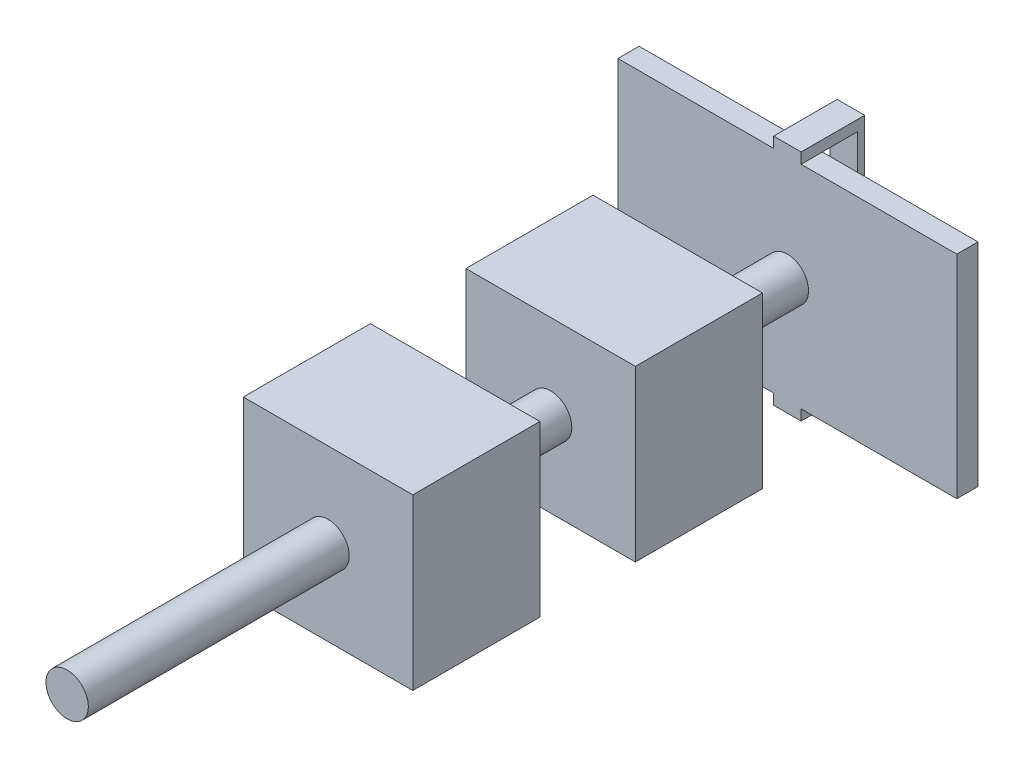
SolidWorks part; units mm, degrees
ref_plane "Front Plane" through (0, 0, 0) normal (0, 0, 1) x (1, 0, 0)
ref_plane "Top Plane" through (0, 0, 0) normal (0, 1, 0) x (1, 0, 0)
ref_plane "Right Plane" through (0, 0, 0) normal (1, 0, 0) x (0, 0, -1)
sketch "Sketch1" plane through (0, 0, 0) normal (0, 0, 1) x (1, 0, 0)
  line L0 (0, 0) -> (0, -20845.1654) construction
  line L1 (0, 0) -> (-20845.1654, 0) construction
  circle A0 centre (0, 0) radius 5
  dimension "D1" = 10
extrude "Boss-Extrude1" add sketch "Sketch1" against normal blind 170
sketch "Sketch2" plane through (0, 0, 0) normal (0, 1, 0) x (1, 0, 0)
  line L0 (0, 170) -> (0, 0) construction
  line L1 (20, 61.5918) -> (-20, 61.5918)
  line L2 (20, 61.5918) -> (20, 91.5918)
  line L3 (20, 91.5918) -> (-20, 91.5918)
  line L4 (-20, 61.5918) -> (-20, 91.5918)
  line L5 (20, 61.5918) -> (-20, 91.5918) construction
  line L6 (20, 91.5918) -> (-20, 61.5918) construction
  line L7 (20, 114.1216) -> (-20, 114.1216)
  line L8 (20, 114.1216) -> (20, 144.1216)
  line L9 (20, 144.1216) -> (-20, 144.1216)
  line L10 (-20, 114.1216) -> (-20, 144.1216)
  line L11 (20, 114.1216) -> (-20, 144.1216) construction
  line L12 (20, 144.1216) -> (-20, 114.1216) construction
  point P0 (0, 76.5918)
  point P5 (0, 129.1216)
  dimension "D1" = 30
  dimension "D2" = 40
  dimension "D3" = 30
  dimension "D4" = 40
extrude "Boss-Extrude2" add sketch "Sketch2" along normal blind 20 and the other way blind 20
sketch "Sketch3" plane through (0, 0, -144.1216) normal (0, 0, -1) x (-1, 0, 0)
  line L1 (17.8814, -18.2528) -> (-17.8814, -18.2528)
  line L2 (17.8814, -18.2528) -> (17.8814, 18.2528)
  line L3 (17.8814, 18.2528) -> (-17.8814, 18.2528)
  line L4 (-17.8814, -18.2528) -> (-17.8814, 18.2528)
  line L5 (17.8814, -18.2528) -> (-17.8814, 18.2528) construction
  line L6 (17.8814, 18.2528) -> (-17.8814, -18.2528) construction
  point P0 (0, 0)
extrude "Cut-Extrude5" cut sketch "Sketch3" against normal blind 16 contours L4 L3 L2 L1
sketch "Sketch5" plane through (0, 0, -128.1216) normal (0, 0, -1) x (-1, 0, 0)
  circle A0 centre (0, 0) radius 5
extrude "Boss-Extrude3" add sketch "Sketch5" along normal blind 16
sketch "Sketch8" plane through (0, 0, -91.5918) normal (0, 0, -1) x (-1, 0, 0)
  line L1 (-17.8814, 18.2528) -> (17.8814, 18.2528)
  line L2 (-17.8814, 18.2528) -> (-17.8814, -18.2528)
  line L3 (-17.8814, -18.2528) -> (17.8814, -18.2528)
  line L4 (17.8814, 18.2528) -> (17.8814, -18.2528)
extrude "Cut-Extrude7" cut sketch "Sketch8" against normal blind 18
sketch "Sketch10" plane through (0, 0, -73.5918) normal (0, 0, -1) x (-1, 0, 0)
  circle A0 centre (0, 0) radius 5
extrude "Boss-Extrude4" add sketch "Sketch10" along normal blind 18
sketch "Sketch11" plane through (0, 0, -170) normal (0, 0, -1) x (-1, 0, 0)
  line L1 (40, -25) -> (-40, -25)
  line L2 (40, -25) -> (40, 25)
  line L3 (40, 25) -> (-40, 25)
  line L4 (-40, -25) -> (-40, 25)
  line L5 (40, -25) -> (-40, 25) construction
  line L6 (40, 25) -> (-40, -25) construction
  point P0 (0, 0)
  dimension "D1" = 80
  dimension "D2" = 50
extrude "Boss-Extrude5" add sketch "Sketch11" along normal blind 5
ref_plane "Plane1" through (0, 0, 0) normal (0, -1, 0) x (-1, 0, 0)
sketch "Sketch12" plane through (0, -25, 0) normal (0, -1, 0) x (1, 0, 0)
  line L4 (40, -170) -> (-40, -170)
  line L5 (-40, -170) -> (-40, -175)
  line L6 (-40, -175) -> (40, -175)
  line L7 (40, -175) -> (40, -170)
  line L8 (40, -170) -> (-40, -170)
  line L9 (-40, -170) -> (-40, -175)
  line L10 (-40, -175) -> (40, -175)
  line L11 (40, -175) -> (40, -170)
  dimension "D1" = 0
ref_plane "Plane2" through (0, 0, -185) normal (0, 0, -1) x (-1, 0, 0)
sketch "Sketch13" plane through (0, 0, -185) normal (0, 0, -1) x (-1, 0, 0)
  line L1 (3.2473, -27.5118) -> (-3.2473, -27.5118)
  line L2 (3.2473, -27.5118) -> (3.2473, 27.5118)
  line L3 (3.2473, 27.5118) -> (-3.2473, 27.5118)
  line L4 (-3.2473, -27.5118) -> (-3.2473, 27.5118)
  line L5 (3.2473, -27.5118) -> (-3.2473, 27.5118) construction
  line L6 (3.2473, 27.5118) -> (-3.2473, -27.5118) construction
  point P0 (0, 0)
sketch "Sketch14" plane through (0, 0, -175) normal (0, 0, -1) x (-1, 0, 0)
  line L4 (-40, 25) -> (-40, -25)
  line L5 (-40, -25) -> (40, -25)
  line L6 (40, -25) -> (40, 25)
  line L7 (40, 25) -> (-40, 25)
  line L8 (-40, 25) -> (-40, -25)
  line L9 (-40, -25) -> (40, -25)
  line L10 (40, -25) -> (40, 25)
  line L11 (40, 25) -> (-40, 25)
  dimension "D1" = 0
extrude "Boss-Extrude6" add sketch "Sketch13" against normal up to surface (15 mm away) up to face at (5, 0, -170)
sketch "Sketch15" plane through (3.2473, 0, 0) normal (1, 0, 0) x (0, 0, -1)
  line L0 (185, -27.5) -> (185, 27.5) construction
  line L1 (170, 27.5118) -> (185, 27.5118)
  line L2 (170, 27.5118) -> (170, 25)
  line L3 (170, 25) -> (185, 25)
  line L4 (185, 27.5118) -> (185, 25)
  line L5 (-2.75, 0) -> (2.75, 0) construction
  line L6 (170, -25) -> (185, -25)
  line L7 (185, -27.5118) -> (185, -25)
  line L8 (170, -27.5118) -> (185, -27.5118)
  line L9 (170, -27.5118) -> (170, -25)
sketch "Sketch16" plane through (3.2473, 0, 0) normal (1, 0, 0) x (0, 0, -1)
  line L0 (170, -25) -> (185, -25) construction
  line L1 (175, 25) -> (183.3444, 25)
  line L2 (175, 25) -> (175, -25)
  line L3 (175, -25) -> (183.3444, -25)
  line L4 (183.3444, 25) -> (183.3444, -25)
extrude "Cut-Extrude9" cut sketch "Sketch16" against normal blind 10
sketch "Sketch17" plane through (0, 0, -185) normal (0, 0, -1) x (-1, 0, 0)
  line L1 (1.625, -4.15) -> (-1.625, -4.15)
  line L2 (1.625, -4.15) -> (1.625, 4.15)
  line L3 (1.625, 4.15) -> (-1.625, 4.15)
  line L4 (-1.625, -4.15) -> (-1.625, 4.15)
  line L5 (1.625, -4.15) -> (-1.625, 4.15) construction
  line L6 (1.625, 4.15) -> (-1.625, -4.15) construction
  point P0 (0, 0)
  dimension "D1" = 8.3
  dimension "D2" = 3.25
extrude "Cut-Extrude10" cut sketch "Sketch17" against normal blind 10
